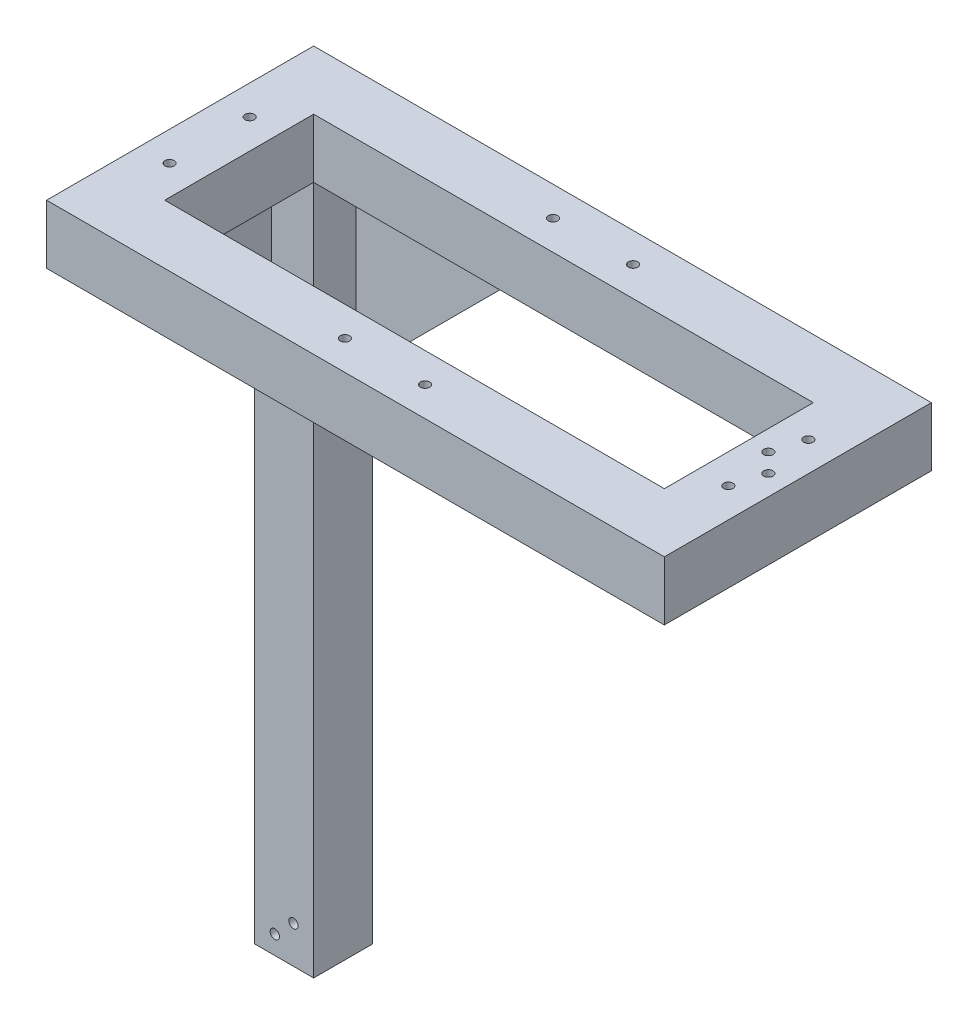
SolidWorks part; units mm, degrees
ref_plane "Plano frontal" through (0, 0, 0) normal (0, 0, 1) x (1, 0, 0)
ref_plane "Plano superior" through (0, 0, 0) normal (0, 1, 0) x (1, 0, 0)
ref_plane "Plano direito" through (0, 0, 0) normal (1, 0, 0) x (0, 0, -1)
sketch "Esboço1" plane through (0, 0, 0) normal (0, 1, 0) x (1, 0, 0)
  line L1 (-165.85, 71.7) -> (165.85, 71.7)
  line L2 (-165.85, 71.7) -> (-165.85, -71.7)
  line L3 (-165.85, -71.7) -> (165.85, -71.7)
  line L4 (165.85, 71.7) -> (165.85, -71.7)
  line L5 (-165.85, 71.7) -> (165.85, -71.7) construction
  line L6 (-165.85, -71.7) -> (165.85, 71.7) construction
  point P0 (0, 0)
  dimension "D1" = 331.7
  dimension "D2" = 143.4
sketch "Esboço3" plane through (0, 0, 0) normal (0, 1, 0) x (1, 0, 0)
  line L1 (-134.15, 40) -> (134.15, 40)
  line L2 (-134.15, 40) -> (-134.15, -40)
  line L3 (-134.15, -40) -> (134.15, -40)
  line L4 (134.15, 40) -> (134.15, -40)
  line L5 (-134.15, 40) -> (134.15, -40) construction
  line L6 (-134.15, -40) -> (134.15, 40) construction
  point P0 (0, 0)
  dimension "D1" = 268.3
  dimension "D2" = 80
extrude "Ressalto-extrusão2" add sketch "Esboço1" along normal blind 31.7
extrude "Corte-extrusão1" cut sketch "Esboço3" along normal blind 31.7
sketch "Esboço4" plane through (0, 0, 0) normal (0, 1, 0) x (1, 0, 0)
  line L0 (165.85, -71.7) -> (165.85, 71.7) construction
  line L1 (-165.85, -71.7) -> (165.85, -71.7) construction
  line L2 (134.15, 40) -> (-134.15, 40) construction
  line L5 (165.85, 71.7) -> (-165.85, 71.7) construction
  line L6 (-165.85, 71.7) -> (-165.85, -71.7) construction
  circle A0 centre (21.5, -55.85) radius 2.5
  circle A1 centre (-21.5, -55.85) radius 2.5
  circle A2 centre (21.5, 55.85) radius 2.5
  circle A3 centre (-21.5, 55.85) radius 2.5
  circle A6 centre (150, -21.5) radius 2.5
  circle A7 centre (150, 21.5) radius 2.5
  circle A8 centre (-150, 21.5) radius 2.5
  circle A9 centre (-150, -21.5) radius 2.5
  circle A10 centre (145, 5) radius 2.5
  circle A11 centre (155, -5) radius 2.5
  dimension "D1" = 5
  dimension "D2" = 5
  dimension "D3" = 5
  dimension "D4" = 5
  dimension "D13" = 5
  dimension "D14" = 15.85
  dimension "D19" = 50.2
  dimension "D21" = 5
  dimension "D5" = 144.35
  dimension "D6" = 43
  dimension "D7" = 144.35
  dimension "D8" = 43
  dimension "D9" = 15.85
  dimension "D10" = 15.85
  dimension "D11" = 15.85
  dimension "D12" = 15.85
  dimension "D15" = 43
  dimension "D16" = 10.85
  dimension "D17" = 10
  dimension "D18" = 66.7
  dimension "D20" = 15.85
  dimension "D22" = 15.85
  dimension "D23" = 50.2
  dimension "D24" = 15.85
  dimension "D25" = 43
  dimension "D26" = 10
extrude "Corte-extrusão2" cut sketch "Esboço4" along normal blind 31.7
sketch "Esboço6" plane through (0, 0, 0) normal (0, 1, 0) x (1, 0, 0)
  line L1 (-134.15, 40) -> (-165.85, 40)
  line L2 (-134.15, 40) -> (-134.15, 71.7)
  line L3 (-134.15, 71.7) -> (-165.85, 71.7)
  line L4 (-165.85, 40) -> (-165.85, 71.7)
extrude "Ressalto-extrusão3" add sketch "Esboço6" against normal blind 370
sketch "Esboço7" plane through (0, 0, 0) normal (0, 0, 1) x (1, 0, 0)
  line L0 (-165.85, -370) -> (-134.15, -370) construction
  line L1 (-134.15, -370) -> (-134.15, 0) construction
  circle A0 centre (-155, -360) radius 2.5
  circle A1 centre (-145, -350) radius 2.5
  point P4 (0, 0)
  point P5 (0, 0)
  point P8 (-144.6884, -350.1378)
  dimension "D1" = 10
  dimension "D2" = 10
  dimension "D3" = 10
  dimension "D4" = 10.85
extrude "Corte-extrusão3" cut sketch "Esboço7" against normal through all
sketch "Esboço8" plane through (0, 0, 0) normal (0, 1, 0) x (1, 0, 0)
  line L0 (-160.85, 66.7) -> (-160.85, -71.7)
  line L1 (-160.7742, 66.7) -> (0, 66.7)
  line L2 (-165.85, 40) -> (-165.85, -71.7) construction
  line L3 (165.85, 71.7) -> (-134.15, 71.7) construction
  dimension "D1" = 5
  dimension "D2" = 5
ref_plane "Plano1" through (-160.85, 0, 0) normal (1, 0, 0) x (0, 0, 1)
sketch "Esboço9" plane through (-160.85, 0, 0) normal (1, 0, 0) x (0, 0, 1)
  line L1 (-40, 0) -> (60, 0)
  line L2 (60, 0) -> (-40, 100)
  line L3 (-40, 100) -> (-40, 0)
  point P4 (0, 0)
  point P5 (0, 0)
  point P6 (0, 0)
  point P7 (0, 0)
  dimension "D1" = 100
  dimension "D2" = 100
extrude "Ressalto-extrusão4" add sketch "Esboço9" along normal blind 4 separate body
ref_plane "Plano2" through (0, 0, -66.7) normal (0, 0, -1) x (1, 0, 0)
sketch "Esboço10" plane through (0, 0, -66.7) normal (0, 0, -1) x (1, 0, 0)
  line L1 (-134.15, 0) -> (-34.15, 0)
  line L2 (-34.15, 0) -> (-134.15, 100)
  line L3 (-134.15, 100) -> (-134.15, 0)
  point P4 (0, 0)
  point P5 (0, 0)
  point P6 (0, 0)
  point P7 (0, 0)
extrude "Ressalto-extrusão5" add sketch "Esboço10" against normal blind 4 separate body
